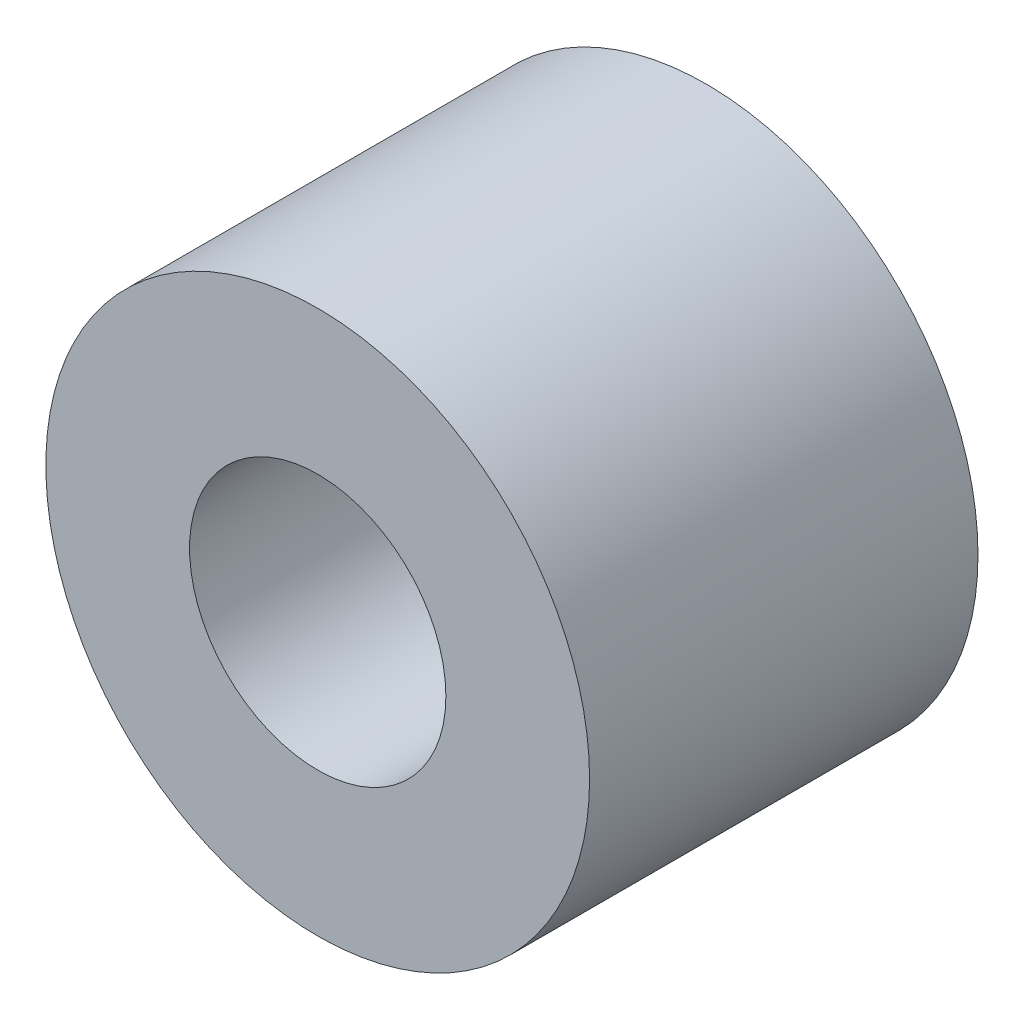
SolidWorks part; units mm, degrees
ref_plane "正面" through (0, 0, 0) normal (0, 0, 1) x (1, 0, 0)
ref_plane "平面" through (0, 0, 0) normal (0, 1, 0) x (1, 0, 0)
ref_plane "右側面" through (0, 0, 0) normal (1, 0, 0) x (0, 0, -1)
sketch "ｽｹｯﾁ1" plane through (0, 0, 0) normal (0, 0, 1) x (1, 0, 0)
  circle A0 centre (0, 0) radius 3.5
  circle A1 centre (0, 0) radius 1.65
  dimension "D1" = 7
  dimension "D2" = 3.3
extrude "ﾎﾞｽ - 押し出し1" add sketch "ｽｹｯﾁ1" along normal blind 5
